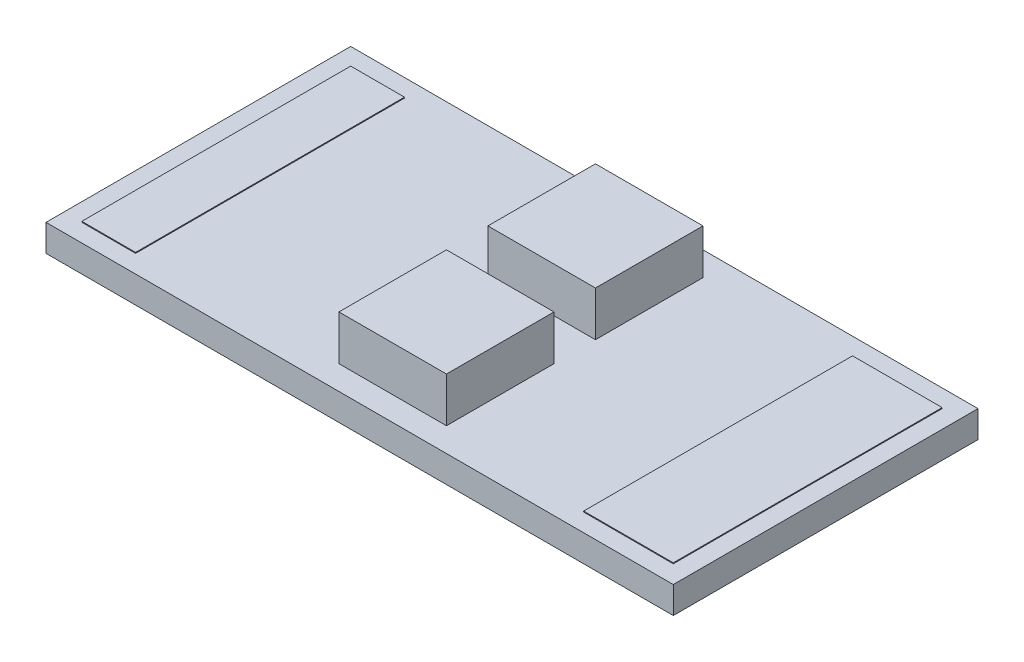
SolidWorks part; units mm, degrees
ref_plane "Спереди" through (0, 0, 0) normal (0, 0, 1) x (1, 0, 0)
ref_plane "Сверху" through (0, 0, 0) normal (0, 1, 0) x (1, 0, 0)
ref_plane "Справа" through (0, 0, 0) normal (1, 0, 0) x (0, 0, -1)
sketch "Эскиз1" plane through (0, 0, 0) normal (0, 1, 0) x (1, 0, 0)
  line L1 (0, 8.5) -> (-35, 8.5)
  line L2 (0, 8.5) -> (0, -8.5)
  line L3 (0, -8.5) -> (-35, -8.5)
  line L4 (-35, 8.5) -> (-35, -8.5)
  point P4 (0, 0)
  dimension "D1" = 17
  dimension "D2" = 35
extrude "Бобышка-Вытянуть1" add sketch "Эскиз1" along normal blind 1.5
sketch "Эскиз2" plane through (0, 0, 0) normal (0, 1, 0) x (1, 0, 0)
  line L1 (0, 7.5) -> (-10, 7.5)
  line L2 (0, 7.5) -> (0, -7.5)
  line L3 (0, -7.5) -> (-10, -7.5)
  line L4 (-10, 7.5) -> (-10, -7.5)
  point P4 (0, 0)
  dimension "D1" = 15
  dimension "D2" = 10
extrude "Бобышка-Вытянуть2" [suppressed] add sketch "Эскиз2" along normal blind 11
chamfer "Фаска1" [suppressed] distance 4 distance2 2
sketch "Эскиз3" [suppressed] plane through (0, 11, 0) normal (0, 1, 0) x (1, 0, 0)
  line L0 (-5, 5.5) -> (-5, -5.5) construction
  line L1 (0, 5.5) -> (-10, 5.5) construction
  line L2 (-10, -5.5) -> (0, -5.5) construction
sketch "Эскиз4" plane through (0, 0, 0) normal (0, 1, 0) x (1, 0, 0)
  line L1 (-20, 7.1566) -> (-14, 7.1566)
  line L2 (-20, 7.1566) -> (-20, 1.1566)
  line L3 (-20, 1.1566) -> (-14, 1.1566)
  line L4 (-14, 7.1566) -> (-14, 1.1566)
  line L9 (0, 0) -> (-35, 0) construction
  line L10 (-35, 8.5) -> (-35, -8.5) construction
  line L11 (-20, -1.1566) -> (-14, -1.1566)
  line L12 (-14, -7.1566) -> (-14, -1.1566)
  line L13 (-20, -7.1566) -> (-14, -7.1566)
  line L14 (-20, -7.1566) -> (-20, -1.1566)
  line L15 (0, 8.5) -> (0, -8.5) construction
  dimension "D1" = 20
  dimension "D2" = 6
extrude "Бобышка-Вытянуть3" add sketch "Эскиз4" along normal blind 4
sketch "Эскиз5" plane through (0, 0, 0) normal (0, 1, 0) x (1, 0, 0)
  line L0 (-35, 0) -> (0, 0)
  line L1 (-35, 8.5) -> (-35, -8.5) construction
sketch "Эскиз6" plane through (0, 0, 0) normal (0, 1, 0) x (1, 0, 0)
  line L0 (-35, -8.5) -> (0, -8.5) construction
  line L1 (0, 8.5) -> (-7, 8.5) construction
  line L2 (0, 8.5) -> (0, -8.5) construction
  line L3 (0, -8.5) -> (-7, -8.5) construction
  line L4 (-7, 8.5) -> (-7, -8.5) construction
  line L5 (-1, 7.5) -> (-6, 7.5)
  line L6 (-35, 8.5) -> (-30, 8.5) construction
  line L7 (-35, 8.5) -> (-35, -8.5) construction
  line L8 (-35, -8.5) -> (-30, -8.5) construction
  line L9 (-30, 8.5) -> (-30, -8.5) construction
  line L10 (-6, 7.5) -> (-6, -7.5)
  line L11 (-1, -7.5) -> (-6, -7.5)
  line L12 (-1, 7.5) -> (-1, -7.5)
  line L13 (-34, 7.5) -> (-31, 7.5)
  line L14 (-31, 7.5) -> (-31, -7.5)
  line L15 (-34, -7.5) -> (-31, -7.5)
  line L16 (-34, 7.5) -> (-34, -7.5)
  dimension "D1" = 7
  dimension "D2" = 5
  dimension "D3" = 1
extrude "Бобышка-Вытянуть4" add sketch "Эскиз6" along normal offset from surface (1.55 mm away) 0.05 up to face at (-17, 1.5, -4.1566) offset beyond the face yes
